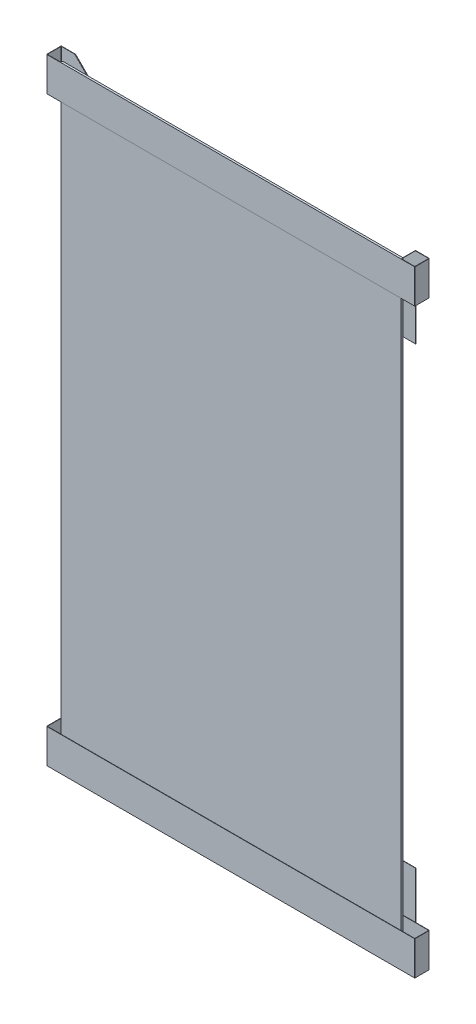
SolidWorks part; units mm, degrees
ref_plane "Front Plane" through (0, 0, 0) normal (0, 0, 1) x (1, 0, 0)
ref_plane "Top Plane" through (0, 0, 0) normal (0, 1, 0) x (1, 0, 0)
ref_plane "Right Plane" through (0, 0, 0) normal (1, 0, 0) x (0, 0, -1)
ref_plane "Plane1" through (0, 0, 0.25) normal (0, 0, 1) x (1, 0, 0)
sketch "Sketch1" plane through (0, 0, 0.25) normal (0, 0, 1) x (1, 0, 0)
  line L0 (25, -42.75) -> (25, 45.25)
  line L1 (25, 45.25) -> (-25, 45.25)
  line L2 (-25, 45.25) -> (-25, -42.75)
  line L3 (-25, -42.75) -> (25, -42.75)
  dimension "D1" = 50
  dimension "D2" = 88
  dimension "D3" = 25
  dimension "D4" = 42.75
extrude "Boss-Extrude1" add sketch "Sketch1" against normal blind 0.25
ref_plane "Plane3" through (0, -45.25, 0) normal (0, -1, 0) x (-1, 0, 0)
sketch "Sketch4" plane through (0, -45.25, 0) normal (0, -1, 0) x (-1, 0, 0)
  line L1 (-26.95, -0.25) -> (26.95, -0.25)
  line L3 (-27, -0.3) -> (27, -0.3)
  line L5 (0, 0) -> (0, 2.5169) construction
  line L6 (25, -0.25) -> (-25, -0.25) construction
  line L7 (-20, 1.85) -> (-20, 1.8)
  line L8 (27, -0.2) -> (27, 1.75)
  line L9 (-26.95, 1.8) -> (-20, 1.8)
  line L10 (27.05, -0.25) -> (27.05, 1.8)
  line L11 (27, 1.85) -> (20, 1.85)
  line L12 (-27, 1.85) -> (-20, 1.85)
  line L13 (26.95, 1.8) -> (20, 1.8)
  line L14 (20, 1.85) -> (20, 1.8)
  line L15 (-27.05, -0.25) -> (-27.05, 1.8)
  line L16 (-27, -0.2) -> (-27, 1.75)
  arc A0 (27, 1.85) -> (27.05, 1.8) centre (27, 1.8) cw
  arc A1 (27, 1.75) -> (26.95, 1.8) centre (26.95, 1.75) ccw
  arc A2 (27, -0.3) -> (27.05, -0.25) centre (27, -0.25) ccw
  arc A3 (26.95, -0.25) -> (27, -0.2) centre (26.95, -0.2) ccw
  arc A4 (-26.95, -0.25) -> (-27, -0.2) centre (-26.95, -0.2) cw
  arc A5 (-27, -0.3) -> (-27.05, -0.25) centre (-27, -0.25) cw
  arc A6 (-27, 1.75) -> (-26.95, 1.8) centre (-26.95, 1.75) cw
  arc A7 (-27, 1.85) -> (-27.05, 1.8) centre (-27, 1.8) ccw
  dimension "D1" = 0.05
  dimension "D2" = 7
  dimension "D3" = 54
  dimension "D4" = 0.05
  dimension "D5" = 0.05
  dimension "D6" = 2.05
extrude "Boss-Extrude2" add sketch "Sketch4" against normal blind 5
sketch "Sketch5" plane through (0, 0, -1.85) normal (0, 0, -1) x (-1, 0, 0)
  line L0 (0, 0) -> (0, -53.2903) construction
  line L1 (20, -45.25) -> (25, -45.25)
  line L2 (20, -45.25) -> (20, -33.35)
  line L3 (20, -33.35) -> (25, -33.35)
  line L4 (25, -45.25) -> (25, -33.35)
  line L5 (-25, -45.25) -> (-25, -33.35)
  line L6 (-20, -33.35) -> (-25, -33.35)
  line L7 (-20, -45.25) -> (-20, -33.35)
  line L8 (-20, -45.25) -> (-25, -45.25)
  dimension "D1" = 5
  dimension "D2" = 11.9
extrude "Boss-Extrude3" add sketch "Sketch5" along normal blind 0.05
sketch "Sketch6" plane through (0, 0, -1.9) normal (0, 0, -1) x (-1, 0, 0)
  line L1 (20, -45.25) -> (25, -45.25)
  line L2 (20, -45.25) -> (20, -40.2549)
  line L3 (0, 0) -> (0, -53.2763) construction
  line L4 (-20, -40.2549) -> (-25, -45.25)
  line L5 (20, -40.2549) -> (25, -45.25)
  line L6 (-20, -45.25) -> (-20, -40.2549)
  line L7 (-20, -45.25) -> (-25, -45.25)
  dimension "D1" = 4.9951
  dimension "D2" = 5
extrude "Cut-Extrude1" cut sketch "Sketch6" against normal blind 0.2
fillet "Fillet1" radius 0.04 4 edges at (-22.5, -42.7525, -1.8) (-22.5, -42.7525, -1.9) (22.5, -42.7525, -1.9) (22.5, -42.7525, -1.8)
sketch "Sketch7" plane through (0, 0, 0.25) normal (0, 0, 1) x (1, 0, 0)
  line L0 (-25, 0) -> (25, 0) construction
  line L1 (-25, 45.25) -> (-25, -40.25) construction
  line L2 (25, -40.25) -> (25, 45.25) construction
  dimension "D1" = 0
ref_plane "Plane4" through (0, 0, 0) normal (0, -1, 0) x (-1, 0, 0)
mirror "Mirror1" about plane through (0, 0, 0) normal (0, -1, 0) of "Boss-Extrude2", "Boss-Extrude3", "Cut-Extrude1", "Fillet1"
